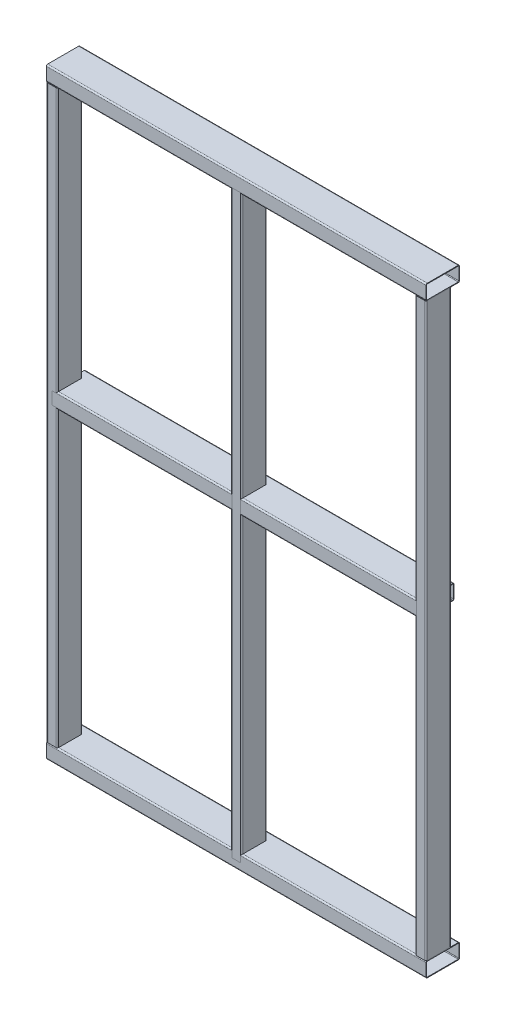
SolidWorks part; units mm, degrees
material "Hierro dúctil"
ref_plane "Alzado" through (0, 0, 0) normal (0, 0, 1) x (1, 0, 0)
ref_plane "Planta" through (0, 0, 0) normal (0, 1, 0) x (1, 0, 0)
ref_plane "Vista lateral" through (0, 0, 0) normal (1, 0, 0) x (0, 0, -1)
sketch "Croquis2" plane through (0, 0, 0) normal (0, 0, 1) x (1, 0, 0)
  line L0 (2200, 0) -> (-2200, 0)
  line L1 (-2200, 3680) -> (2200, 3680)
  line L2 (-2200, 7000) -> (2200, 7000)
  line L3 (-2200, 7000) -> (-2200, 0)
  line L4 (2200, 7000) -> (2200, 0)
  line L5 (0, 7000) -> (0, 0)
  point P4 (0, 0)
  dimension "D1" = 3680
  dimension "D2" = 4400
  dimension "D3" = 7000
other "Tubo rectangular 120 X 80 X 8(1)"
ref_plane "Plano1" through (2200, 0, 0) normal (-1, 0, 0) x (0, -1, 0)
sketch "Sketch1" plane through (2200, 0, 0) normal (-1, 0, 0) x (0, -1, 0)
  line L0 (-74, -192) -> (74, -192)
  line L1 (-82, -184) -> (-82, 184)
  line L2 (74, 192) -> (-74, 192)
  line L3 (82, 184) -> (82, -184)
  line L4 (-74, -200) -> (74, -200)
  line L5 (-90, -184) -> (-90, 184)
  line L6 (74, 200) -> (-74, 200)
  line L7 (90, 184) -> (90, -184)
  arc A0 (90, 184) -> (74, 200) centre (74, 184) ccw
  arc A1 (74, -200) -> (90, -184) centre (74, -184) ccw
  arc A2 (-90, -184) -> (-74, -200) centre (-74, -184) ccw
  arc A3 (-74, 200) -> (-90, 184) centre (-74, 184) ccw
  arc A4 (-74, 192) -> (-82, 184) centre (-74, 184) ccw
  arc A5 (82, 184) -> (74, 192) centre (74, 184) ccw
  arc A6 (74, -192) -> (82, -184) centre (74, -184) ccw
  arc A7 (-82, -184) -> (-74, -192) centre (-74, -184) ccw
  point P0 (0, 200)
  point P1 (90, 0)
  point P2 (0, -200)
  point P3 (-90, 0)
  point P4 (-90, 200)
  point P5 (90, 200)
  point P6 (90, -200)
  point P7 (-90, -200)
  point P8 (0, 0)
  point P33 (0, 0)
  dimension "D1" = 16
  dimension "Thickness" = 8
  dimension "V_leg" = 400
  dimension "H_leg" = 180
ref_plane "Plano3" through (0, 0, 50) normal (0, 0, 1) x (1, 0, 0)
sketch "Croquis7" plane through (0, 0, 50) normal (0, 0, 1) x (1, 0, 0)
  line L0 (0, 7000) -> (0, 0) construction
  line L1 (-2200, 3680) -> (2200, 3680) construction
  line L2 (0, 7000) -> (0, 0)
  line L3 (-2200, 3680) -> (2200, 3680)
  line L4 (-2200, 0) -> (2200, 0)
  line L5 (-2200, 7000) -> (-2200, 0)
  line L6 (2200, 7000) -> (-2200, 7000)
  line L7 (2200, 0) -> (2200, 7000)
  line L8 (-2200, 0) -> (2200, 0)
  line L9 (-2200, 7000) -> (-2200, 0)
  line L10 (2200, 7000) -> (-2200, 7000)
  line L11 (2200, 0) -> (2200, 7000)
  dimension "D1" = 0
other "Tubo rectangular 120 X 80 X 8(2)"
ref_plane "Plano4" through (-2200, 7000, 50) normal (0, -1, 0) x (1, 0, 0)
sketch "Sketch13" plane through (-2200, 7000, 50) normal (0, -1, 0) x (1, 0, 0)
  line L0 (-49, -142) -> (49, -142)
  line L1 (-57, -134) -> (-57, 134)
  line L2 (49, 142) -> (-49, 142)
  line L3 (57, 134) -> (57, -134)
  line L4 (-49, -150) -> (49, -150)
  line L5 (-65, -134) -> (-65, 134)
  line L6 (49, 150) -> (-49, 150)
  line L7 (65, 134) -> (65, -134)
  arc A0 (65, 134) -> (49, 150) centre (49, 134) ccw
  arc A1 (49, -150) -> (65, -134) centre (49, -134) ccw
  arc A2 (-65, -134) -> (-49, -150) centre (-49, -134) ccw
  arc A3 (-49, 150) -> (-65, 134) centre (-49, 134) ccw
  arc A4 (-49, 142) -> (-57, 134) centre (-49, 134) ccw
  arc A5 (57, 134) -> (49, 142) centre (49, 134) ccw
  arc A6 (49, -142) -> (57, -134) centre (49, -134) ccw
  arc A7 (-57, -134) -> (-49, -142) centre (-49, -134) ccw
  point P0 (0, 150)
  point P1 (65, 0)
  point P2 (0, -150)
  point P3 (-65, 0)
  point P4 (-65, 150)
  point P5 (65, 150)
  point P6 (65, -150)
  point P7 (-65, -150)
  point P8 (0, 0)
  point P33 (0, 0)
  dimension "D1" = 16
  dimension "Thickness" = 8
  dimension "V_leg" = 300
  dimension "H_leg" = 130
other "Recortar/Extender1"
other "Recortar/Extender2"
other "Recortar/Extender3"
other "Recortar/Extender4"
